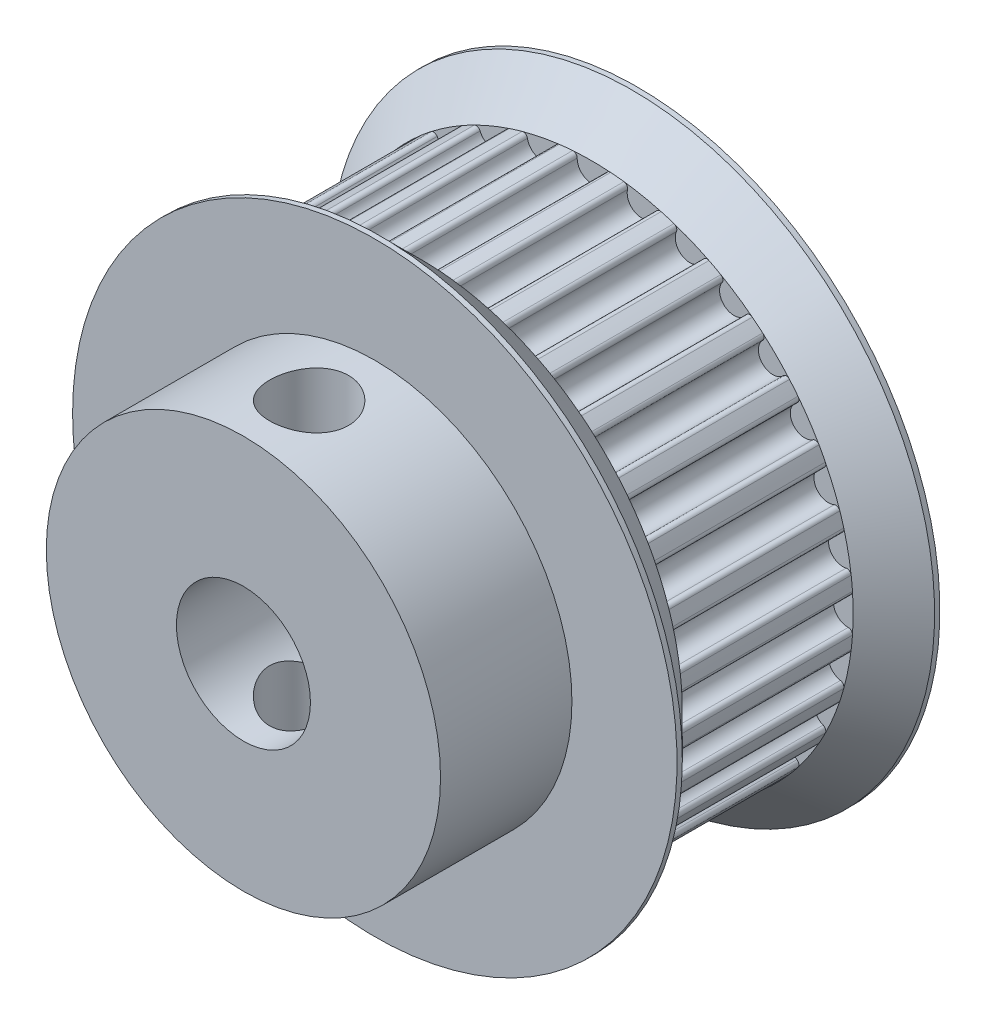
SolidWorks part; units mm, degrees
other "Camera1"
other "Camera2"
other "Camera3"
ref_plane "Front" through (0, 0, 0) normal (0, 0, 1) x (1, 0, 0)
ref_plane "Top" through (0, 0, 0) normal (0, 1, 0) x (1, 0, 0)
ref_plane "Right" through (0, 0, 0) normal (1, 0, 0) x (0, 0, -1)
sketch "Sketch1" plane through (0, 0, 0) normal (1, 0, 0) x (0, 0, -1)
  line L0 (0, 0) -> (-24.4032, 0) construction
  line L4 (-1.75, 9.95) -> (-8.25, 9.95)
  line L5 (-10, 11.5) -> (-10, 2.55)
  line L6 (-10, 2.55) -> (0, 2.55)
  line L7 (0, 2.55) -> (0, 11.5)
  line L9 (-0.2, 11.5) -> (-1.75, 9.95)
  line L11 (-5, 9.95) -> (-5, 22.0506) construction
  line L12 (-9.8, 11.5) -> (-8.25, 9.95)
  line L17 (-10, 11.5) -> (-9.8, 11.5)
  line L18 (-0.2, 11.5) -> (0, 11.5)
  dimension "D1" = 135
  dimension "D2" = 10
  dimension "D3" = 6.5
  dimension "D4" = 19.9
  dimension "D5" = 23
  dimension "D8" = 5.1
revolve "Revolve1" add sketch "Sketch1" angle 360 about L0
ref_plane "Plane2" through (0, 0, 1.75) normal (0, 0, 1) x (1, 0, 0)
ref_plane "Plane3" through (0, 0, 8.25) normal (0, 0, 1) x (1, 0, 0)
sketch "Sketch2" plane through (0, 0, 1.75) normal (0, 0, 1) x (1, 0, 0)
  circle A0 centre (0, 9.75) radius 0.55
  circle A2 centre (1.9021, 9.5627) radius 0.55
  circle A3 centre (3.7312, 9.0078) radius 0.55
  circle A4 centre (5.4168, 8.1068) radius 0.55
  circle A5 centre (6.8943, 6.8943) radius 0.55
  circle A6 centre (8.1068, 5.4168) radius 0.55
  circle A7 centre (9.0078, 3.7312) radius 0.55
  circle A8 centre (9.5627, 1.9021) radius 0.55
  circle A9 centre (9.75, 0) radius 0.55
  circle A10 centre (9.5627, -1.9021) radius 0.55
  circle A11 centre (9.0078, -3.7312) radius 0.55
  circle A12 centre (8.1068, -5.4168) radius 0.55
  circle A13 centre (6.8943, -6.8943) radius 0.55
  circle A14 centre (5.4168, -8.1068) radius 0.55
  circle A15 centre (3.7312, -9.0078) radius 0.55
  circle A16 centre (1.9021, -9.5627) radius 0.55
  circle A17 centre (0, -9.75) radius 0.55
  circle A18 centre (-1.9021, -9.5627) radius 0.55
  circle A19 centre (-3.7312, -9.0078) radius 0.55
  circle A20 centre (-5.4168, -8.1068) radius 0.55
  circle A21 centre (-6.8943, -6.8943) radius 0.55
  circle A22 centre (-8.1068, -5.4168) radius 0.55
  circle A23 centre (-9.0078, -3.7312) radius 0.55
  circle A24 centre (-9.5627, -1.9021) radius 0.55
  circle A25 centre (-9.75, 0) radius 0.55
  circle A26 centre (-9.5627, 1.9021) radius 0.55
  circle A27 centre (-9.0078, 3.7312) radius 0.55
  circle A28 centre (-8.1068, 5.4168) radius 0.55
  circle A29 centre (-6.8943, 6.8943) radius 0.55
  circle A30 centre (-5.4168, 8.1068) radius 0.55
  circle A31 centre (-3.7312, 9.0078) radius 0.55
  circle A32 centre (-1.9021, 9.5627) radius 0.55
  point P68 (0, 0)
  dimension "D1" = 1.1
  dimension "D2" = 9.75
  dimension "D3" = 32
extrude "Cut-Extrude1" cut sketch "Sketch2" along normal up to surface (6.5 mm away) up to plane "Plane3"
fillet "Fillet1" radius 0.16 64 edges at (-5.9506, 7.9745, 5) (-5.0902, 8.5494, 5) (-7.3921, 6.6603, 5) (-6.6603, 7.3921, 5) (-8.5494, 5.0902, 5) (-7.9745, 5.9506, 5) (-9.3782, 3.3245, 5) (-8.9822, 4.2806, 5) (-9.8466, 1.4311, 5) (-9.6447, 2.446, 5) (-9.9365, -0.5174, 5) (-9.9365, 0.5174, 5) (-9.6447, -2.446, 5) (-9.8466, -1.4311, 5) (-8.9822, -4.2806, 5) (-9.3782, -3.3245, 5) (-7.9745, -5.9506, 5) (-8.5494, -5.0902, 5) (-6.6603, -7.3921, 5) (-7.3921, -6.6603, 5) (-5.0902, -8.5494, 5) (-5.9506, -7.9745, 5) (-3.3245, -9.3782, 5) (-4.2806, -8.9822, 5) (-1.4311, -9.8466, 5) (-2.446, -9.6447, 5) (0.5174, -9.9365, 5) (-0.5174, -9.9365, 5) (2.446, -9.6447, 5) (1.4311, -9.8466, 5) (4.2806, -8.9822, 5) (3.3245, -9.3782, 5) (5.9506, -7.9745, 5) (5.0902, -8.5494, 5) (7.3921, -6.6603, 5) (6.6603, -7.3921, 5) (8.5494, -5.0902, 5) (7.9745, -5.9506, 5) (9.3782, -3.3245, 5) (8.9822, -4.2806, 5) (9.8466, -1.4311, 5) (9.6447, -2.446, 5) (9.9365, 0.5174, 5) (9.9365, -0.5174, 5) (9.6447, 2.446, 5) (9.8466, 1.4311, 5) (8.9822, 4.2806, 5) (9.3782, 3.3245, 5) (7.9745, 5.9506, 5) (8.5494, 5.0902, 5) (6.6603, 7.3921, 5) (7.3921, 6.6603, 5) (5.0902, 8.5494, 5) (5.9506, 7.9745, 5) (3.3245, 9.3782, 5) (4.2806, 8.9822, 5) (1.4311, 9.8466, 5) (2.446, 9.6447, 5) (-0.5174, 9.9365, 5) (0.5174, 9.9365, 5) (-2.446, 9.6447, 5) (-1.4311, 9.8466, 5) (-4.2806, 8.9822, 5) (-3.3245, 9.3782, 5)
sketch "Sketch3" plane through (0, 0, 10) normal (0, 0, 1) x (1, 0, 0)
  circle A0 centre (0, 0) radius 2.55
  circle A1 centre (0, 0) radius 7.5
  circle A2 centre (0, 0) radius 2.55 construction
  dimension "D1" = 15
extrude "Boss-Extrude1" add sketch "Sketch3" along normal blind 5
sketch "Sketch4" plane through (0, 0, 0) normal (0, 1, 0) x (1, 0, 0)
  line L0 (-2.55, -15) -> (2.55, -15) construction
  circle A0 centre (0, -12.5) radius 1.5
  dimension "D2" = 3
  dimension "D1" = 2.5
extrude "Cut-Extrude2" cut sketch "Sketch4" against normal through all both and the other way through all
